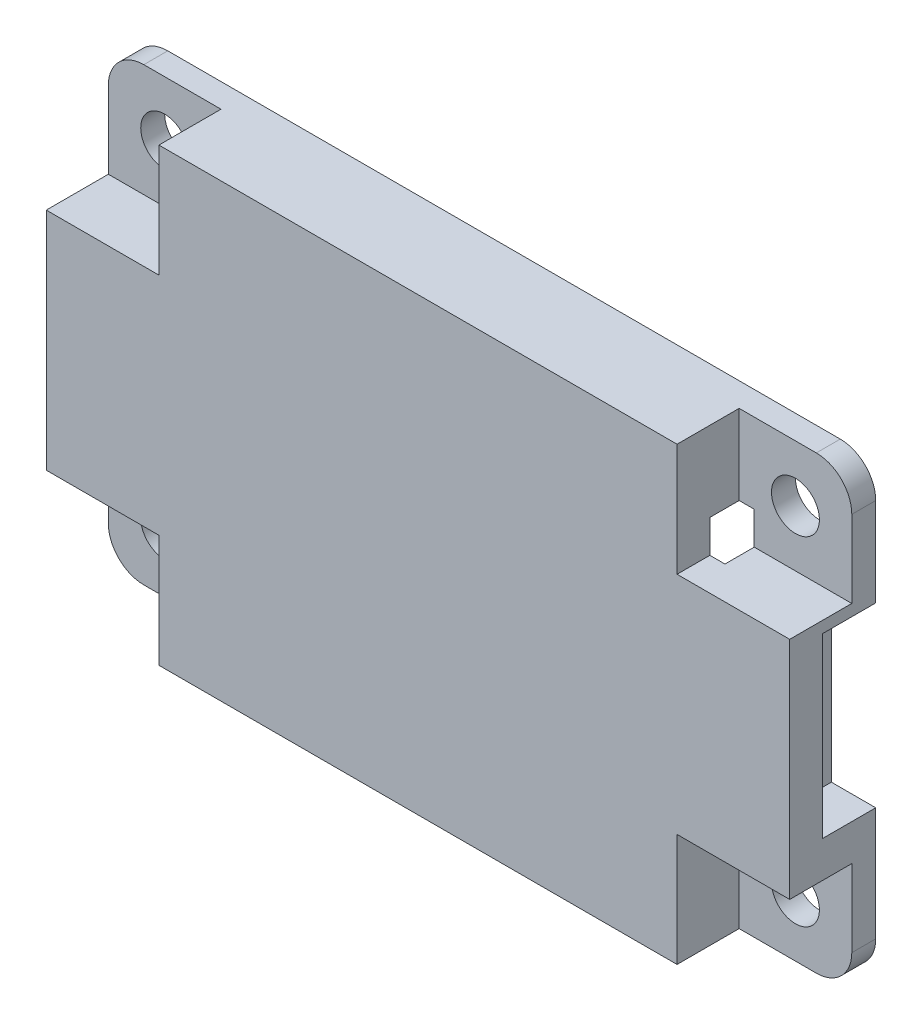
SolidWorks part; units mm, degrees
ref_plane "Front Plane" through (0, 0, 0) normal (0, 0, 1) x (1, 0, 0)
ref_plane "Top Plane" through (0, 0, 0) normal (0, 1, 0) x (1, 0, 0)
ref_plane "Right Plane" through (0, 0, 0) normal (1, 0, 0) x (0, 0, -1)
sketch "Sketch1" plane through (0, 0, 0) normal (0, 0, 1) x (1, 0, 0)
  line L4 (-2, 0) -> (-39.91, 0)
  line L5 (-41.91, -2) -> (-41.91, -23.4)
  line L6 (-39.91, -25.4) -> (-2, -25.4)
  line L7 (0, -23.4) -> (0, -2)
  line L8 (-2, 0) -> (-39.91, 0)
  line L9 (-41.91, -2) -> (-41.91, -23.4)
  line L10 (-39.91, -25.4) -> (-2, -25.4)
  line L11 (0, -23.4) -> (0, -2)
  circle A0 centre (-38.735, -22.225) radius 1.35 construction
  circle A1 centre (-38.735, -3.175) radius 1.35 construction
  circle A2 centre (-3.175, -3.175) radius 1.35 construction
  circle A3 centre (-3.175, -22.225) radius 1.35 construction
  arc A4 (-39.91, 0) -> (-41.91, -2) centre (-39.91, -2) ccw
  arc A5 (-41.91, -23.4) -> (-39.91, -25.4) centre (-39.91, -23.4) ccw
  arc A6 (-2, -25.4) -> (0, -23.4) centre (-2, -23.4) ccw
  arc A7 (0, -2) -> (-2, 0) centre (-2, -2) ccw
  arc A8 (-39.91, 0) -> (-41.91, -2) centre (-39.91, -2) ccw
  arc A9 (-41.91, -23.4) -> (-39.91, -25.4) centre (-39.91, -23.4) ccw
  arc A10 (-2, -25.4) -> (0, -23.4) centre (-2, -23.4) ccw
  arc A11 (0, -2) -> (-2, 0) centre (-2, -2) ccw
  circle A12 centre (-38.735, -22.225) radius 1.35
  circle A13 centre (-38.735, -3.175) radius 1.35
  circle A14 centre (-3.175, -3.175) radius 1.35
  circle A15 centre (-3.175, -22.225) radius 1.35
  dimension "D1" = 0
extrude "Boss-Extrude1" add sketch "Sketch1" along normal up to surface (4.85 mm away)
sketch "Sketch2" plane through (0, 0, 0) normal (0, 0, -1) x (-1, 0, 0)
  line L0 (0, -23.4) -> (0, -2) construction
  line L1 (2.5, -7) -> (0, -7)
  line L2 (2.5, -7) -> (2.5, -17)
  line L3 (2.5, -17) -> (0, -17)
  line L4 (0, -7) -> (0, -17)
  line L5 (2, 0) -> (39.91, 0) construction
  line L6 (41.91, -2) -> (41.91, -23.4) construction
  line L7 (5.5, -4.5) -> (15.5, -4.5)
  line L8 (5.5, -4.5) -> (5.5, -19.5)
  line L9 (5.5, -19.5) -> (15.5, -19.5)
  line L10 (15.5, -4.5) -> (15.5, -19.5)
  line L11 (35.61, -7) -> (38.11, -7)
  line L12 (35.61, -7) -> (35.61, -17)
  line L13 (35.61, -17) -> (38.11, -17)
  line L14 (38.11, -7) -> (38.11, -17)
  dimension "D1" = 7
  dimension "D2" = 10
  dimension "D3" = 2.5
  dimension "D4" = 10
  dimension "D5" = 15
  dimension "D6" = 5.5
  dimension "D7" = 4.5
  dimension "D8" = 2.5
  dimension "D9" = 10
  dimension "D10" = 7
  dimension "D11" = 3.8
extrude "Cut-Extrude1" cut sketch "Sketch2" against normal blind 3
sketch "Sketch4" plane through (0, 0, 4.85) normal (0, 0, 1) x (1, 0, 0)
  line L0 (-39.91, 0) -> (-2, 0) construction
  line L1 (-35.56, 0) -> (-41.91, 0)
  line L2 (-35.56, 0) -> (-35.56, -6.35)
  line L3 (-35.56, -6.35) -> (-41.91, -6.35)
  line L4 (-41.91, 0) -> (-41.91, -6.35)
  line L5 (-35.56, 0) -> (-41.91, -6.35) construction
  line L6 (-35.56, -6.35) -> (-41.91, 0) construction
  line L7 (-35.56, -19.05) -> (-41.91, -19.05)
  line L8 (-35.56, -19.05) -> (-35.56, -25.4)
  line L9 (-35.56, -25.4) -> (-41.91, -25.4)
  line L10 (-41.91, -19.05) -> (-41.91, -25.4)
  line L11 (-35.56, -19.05) -> (-41.91, -25.4) construction
  line L12 (-35.56, -25.4) -> (-41.91, -19.05) construction
  line L13 (0, -19.05) -> (-6.35, -19.05)
  line L14 (0, -19.05) -> (0, -25.4)
  line L15 (0, -25.4) -> (-6.35, -25.4)
  line L16 (-6.35, -19.05) -> (-6.35, -25.4)
  line L17 (0, -19.05) -> (-6.35, -25.4) construction
  line L18 (0, -25.4) -> (-6.35, -19.05) construction
  line L19 (0, 0) -> (-6.35, 0)
  line L20 (0, 0) -> (0, -6.35)
  line L21 (0, -6.35) -> (-6.35, -6.35)
  line L22 (-6.35, 0) -> (-6.35, -6.35)
  line L23 (0, 0) -> (-6.35, -6.35) construction
  line L24 (0, -6.35) -> (-6.35, 0) construction
  point P0 (-38.735, -3.175)
  point P6 (-38.735, -22.225)
  point P12 (-3.175, -22.225)
  point P18 (-3.175, -3.175)
extrude "Cut-Extrude3" cut sketch "Sketch4" against normal blind 3.5
